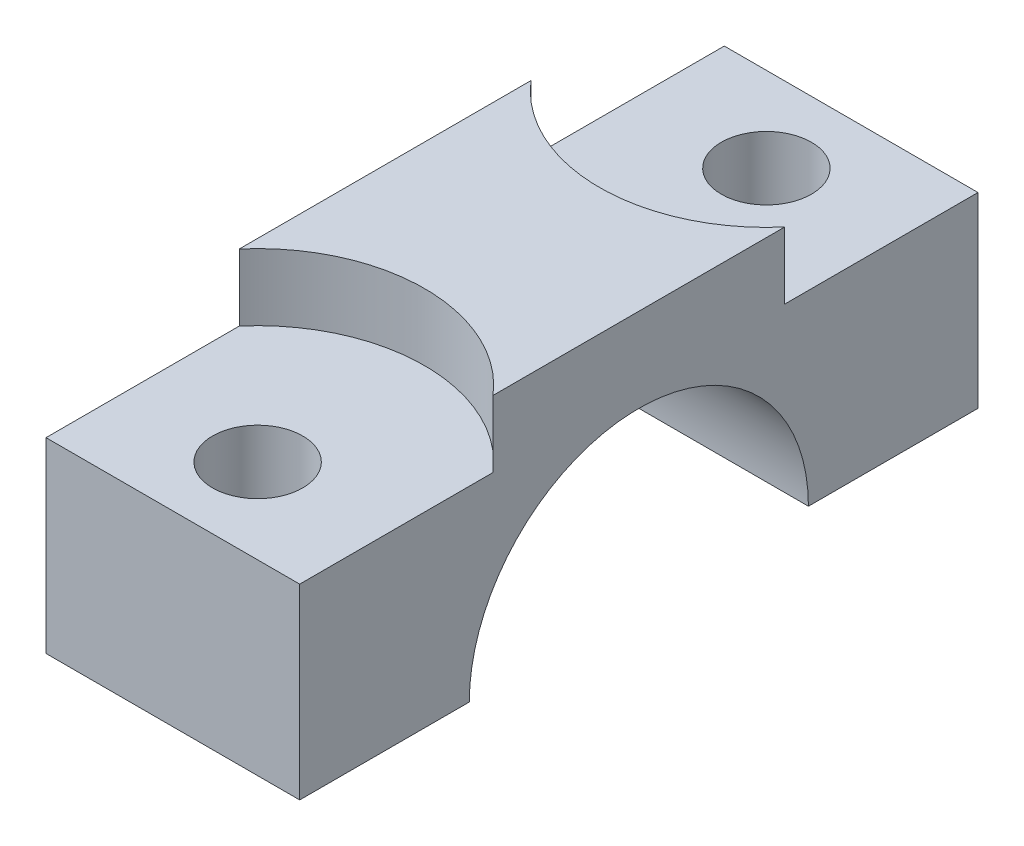
SolidWorks part; units mm, degrees
ref_plane "Front Plane" through (0, 0, 0) normal (0, 0, 1) x (1, 0, 0)
ref_plane "Top Plane" through (0, 0, 0) normal (0, 1, 0) x (1, 0, 0)
ref_plane "Right Plane" through (0, 0, 0) normal (1, 0, 0) x (0, 0, -1)
sketch "Sketch1" plane through (0, 0, 0) normal (1, 0, 0) x (0, 0, -1)
  line L0 (12.7, 0) -> (25.4, 0)
  line L1 (-25.4, 0) -> (-12.7, 0)
  line L2 (-25.4, 0) -> (-25.4, 19)
  line L3 (-25.4, 19) -> (25.4, 19)
  line L4 (25.4, 0) -> (25.4, 19)
  arc A0 (12.7, 0) -> (-12.7, 0) centre (0, 0) ccw
  dimension "D3" = 12.7
  dimension "D1" = 50.8
  dimension "D2" = 19
extrude "Boss-Extrude1" add sketch "Sketch1" along normal mid plane 19
sketch "Sketch2" plane through (0, 0, 0) normal (0, -1, 0) x (1, 0, 0)
  line L0 (-9.5, 19.05) -> (9.5, 19.05) construction
  line L1 (-9.5, 25.4) -> (-9.5, 12.7) construction
  line L2 (9.5, 25.4) -> (9.5, 12.7) construction
  line L3 (-9.5, -19.05) -> (9.5, -19.05) construction
  line L6 (-9.5, -12.7) -> (-9.5, -25.4) construction
  line L7 (9.5, -12.7) -> (9.5, -25.4) construction
  point P12 (0, 19.05)
  point P13 (0, -19.05)
hole_wizard "CBORE for M12 Hex Head Cap Screw1" positions "Sketch3" profile "Sketch4" counterbore size "M12" standard "ISO" end condition through all
sketch "Sketch3" plane through (0, 19, 0) normal (0, 1, 0) x (1, 0, 0)
  point P0 (0, 19.05)
  point P3 (0, -19.05)
sketch "Sketch4" plane through (0, 19, -19.05) normal (1, 0, 0) x (0, 0, 1)
  line L0 (0, 0) -> (0, 19)
  line L1 (0, 19) -> (3.375, 19)
  line L3 (3.375, 19) -> (3.375, 5)
  line L4 (3.375, 5) -> (12.5, 5)
  line L5 (12.5, 5) -> (12.5, 0)
  line L7 (12.5, 0) -> (0, 0)
  line L11 (0, -6.35) -> (0, 107.95) construction
  dimension "Thru Hole Dia." = 6.75
  dimension "Thru Hole Depth" = 19
  dimension "C'Bore Dia." = 25
  dimension "C'Bore Depth" = 5
